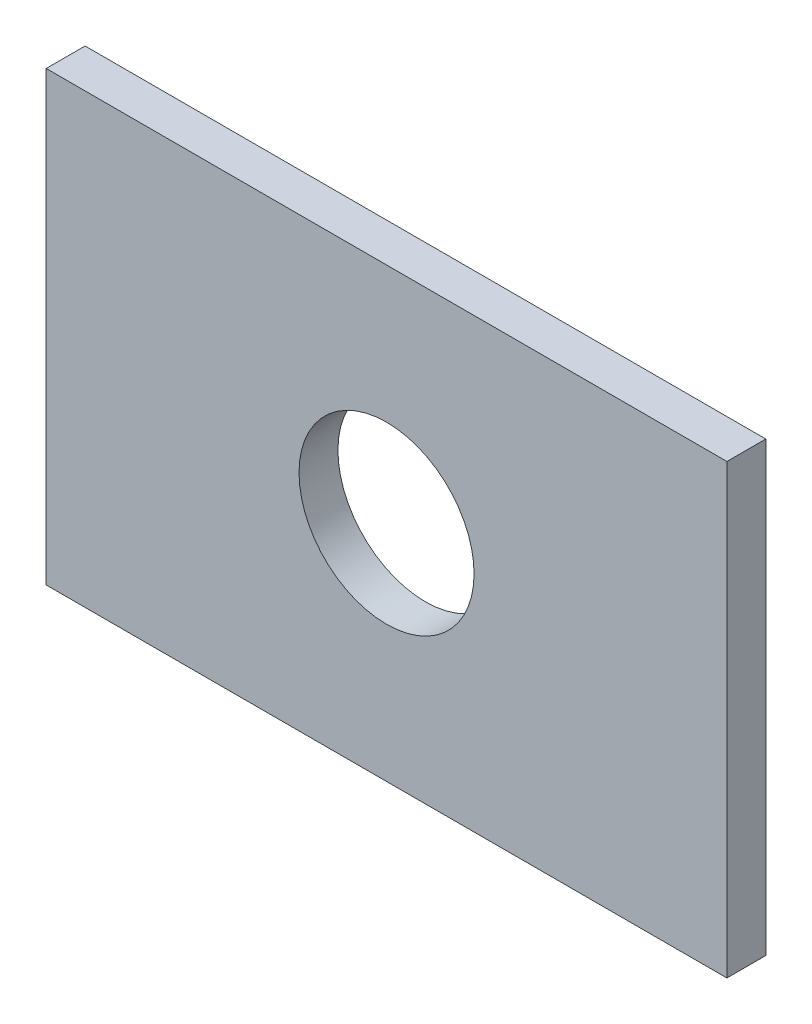
SolidWorks part; units mm, degrees
ref_plane "Front Plane" through (0, 0, 0) normal (0, 0, 1) x (1, 0, 0)
ref_plane "Top Plane" through (0, 0, 0) normal (0, 1, 0) x (1, 0, 0)
ref_plane "Right Plane" through (0, 0, 0) normal (1, 0, 0) x (0, 0, -1)
sketch "Sketch1" plane through (0, 0, 0) normal (0, 0, 1) x (1, 0, 0)
  line L1 (-17.5, -11.5) -> (17.5, -11.5)
  line L2 (-17.5, -11.5) -> (-17.5, 11.5)
  line L3 (-17.5, 11.5) -> (17.5, 11.5)
  line L4 (17.5, -11.5) -> (17.5, 11.5)
  line L5 (-17.5, -11.5) -> (17.5, 11.5) construction
  line L6 (-17.5, 11.5) -> (17.5, -11.5) construction
  circle A0 centre (0, 0) radius 4.5
  dimension "D3" = 9
  dimension "D1" = 35
  dimension "D2" = 23
extrude "Boss-Extrude1" add sketch "Sketch1" along normal blind 2
